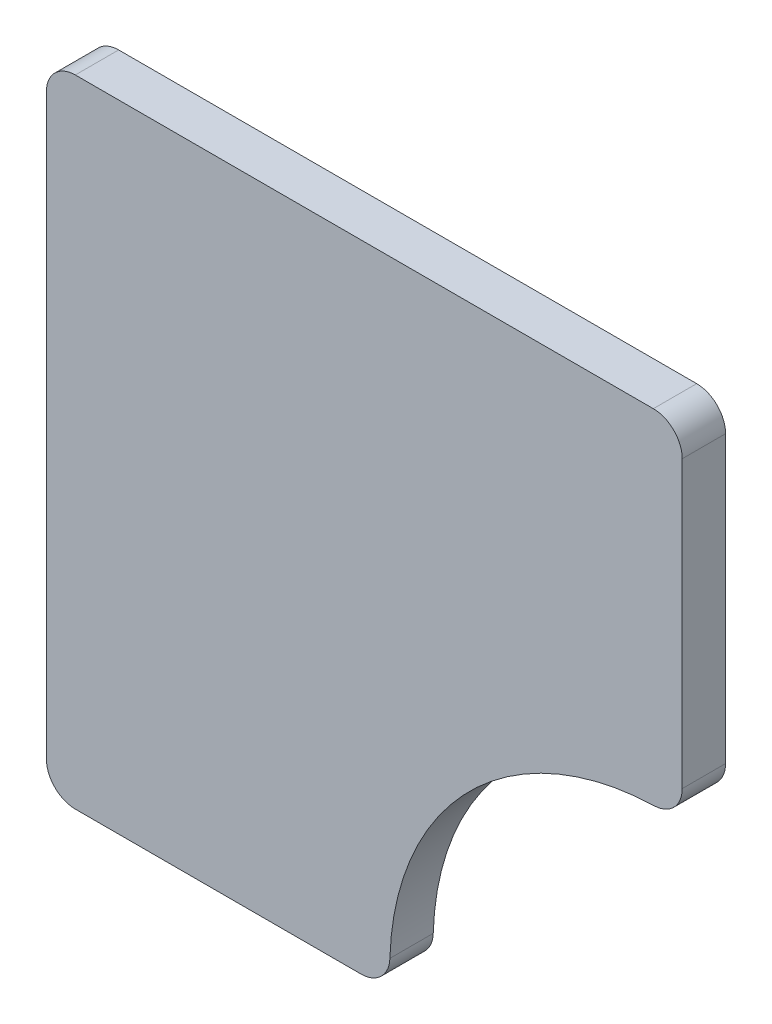
SolidWorks part; units mm, degrees
ref_plane "Front Plane" through (0, 0, 0) normal (0, 0, 1) x (1, 0, 0)
ref_plane "Top Plane" through (0, 0, 0) normal (0, 1, 0) x (1, 0, 0)
ref_plane "Right Plane" through (0, 0, 0) normal (1, 0, 0) x (0, 0, -1)
sketch "Sketch1" plane through (0, 0, 0) normal (0, 0, 1) x (1, 0, 0)
  line L0 (-307.1846, 613.7145) -> (-347.1846, 613.7145)
  line L1 (-349.1846, 611.7145) -> (-349.1846, 571.7145)
  line L2 (-347.1846, 569.7145) -> (-327.4147, 569.7145)
  line L3 (-305.1846, 591.9447) -> (-305.1846, 611.7145)
  arc A0 (-307.1246, 589.9456) -> (-325.4156, 571.6545) centre (-306.559, 571.0889) ccw
  arc A1 (-307.1246, 589.9456) -> (-305.1846, 591.9447) centre (-307.1846, 591.9447) ccw
  arc A3 (-327.4147, 569.7145) -> (-325.4156, 571.6545) centre (-327.4147, 571.7145) ccw
  arc A4 (-307.1846, 613.7145) -> (-305.1846, 611.7145) centre (-307.1846, 611.7145) cw
  arc A5 (-347.1846, 569.7145) -> (-349.1846, 571.7145) centre (-347.1846, 571.7145) cw
  arc A6 (-349.1846, 611.7145) -> (-347.1846, 613.7145) centre (-347.1846, 611.7145) cw
  dimension "D1" = 2
extrude "Boss-Extrude1" add sketch "Sketch1" along normal blind 3
